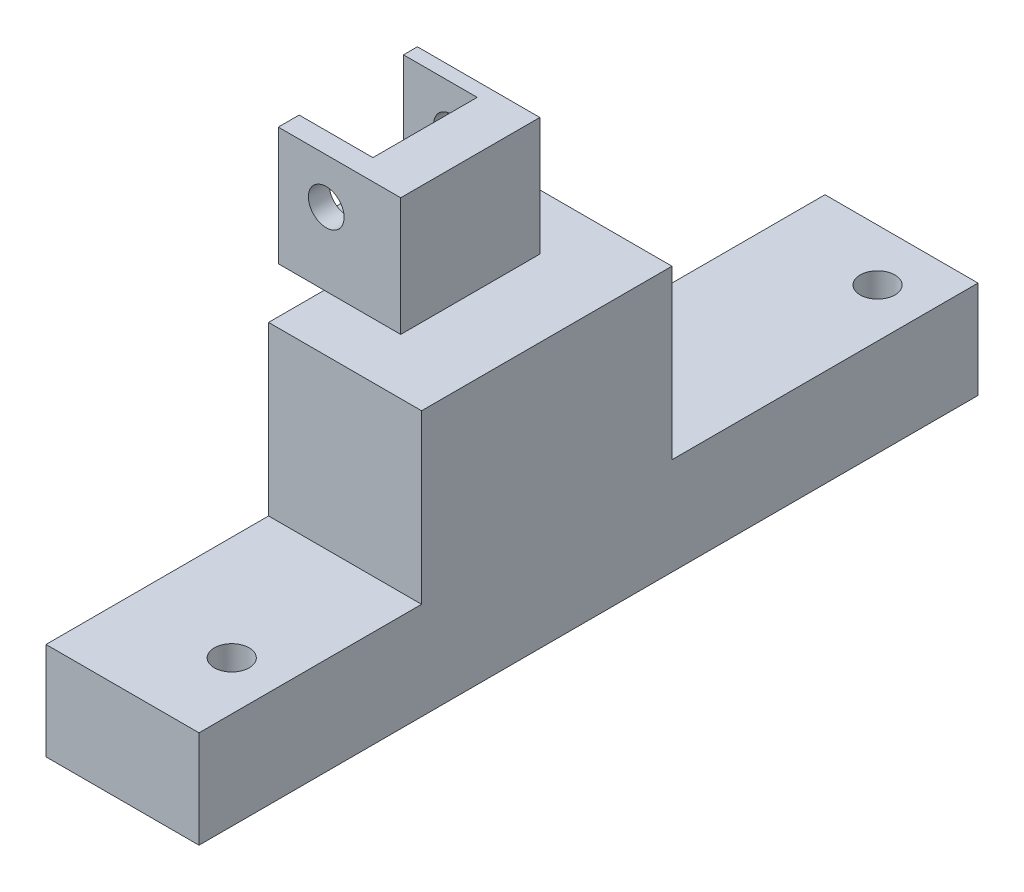
SolidWorks part; units mm, degrees
ref_plane "Front Plane" through (0, 0, 0) normal (0, 0, 1) x (1, 0, 0)
ref_plane "Top Plane" through (0, 0, 0) normal (0, 1, 0) x (1, 0, 0)
ref_plane "Right Plane" through (0, 0, 0) normal (1, 0, 0) x (0, 0, -1)
sketch "Sketch1" plane through (0, 0, 0) normal (0, 0, 1) x (1, 0, 0)
  line L0 (792.5838, 374.5748) -> (792.5838, 352.9594)
  line L1 (806.0458, 374.5748) -> (775.9383, 374.5748) construction
  line L2 (792.5838, 352.9594) -> (814.9358, 352.9594)
  line L3 (814.9358, 352.9594) -> (814.9358, 374.5748)
  line L4 (814.9358, 374.5748) -> (792.5838, 374.5748)
  line L5 (792.5838, 356.7694) -> (801.3383, 356.7694)
  line L6 (801.3383, 356.7694) -> (791.1783, 356.7694) construction
  circle A1 centre (801.3383, 366.2944) radius 3.2639
  arc A2 (801.3383, 356.7694) -> (806.0458, 358.014) centre (801.3383, 366.2944) ccw
  arc A3 (806.0458, 358.014) -> (806.0458, 374.5748) centre (801.3383, 366.2944) ccw
  dimension "D4" = 6.5278
  dimension "D1" = 3.81
  dimension "D2" = 22.352
  dimension "D3" = 8.89
extrude "Boss-Extrude1" add sketch "Sketch1" against normal blind 21.59 contours A3 A2 L5 L0 L2 L3 L4
sketch "Sketch2" plane through (0, 0, 0) normal (0, 0, 1) x (1, 0, 0)
  line L0 (792.5838, 352.9594) -> (792.5838, 374.5748)
  line L1 (806.0458, 374.5748) -> (775.9383, 374.5748) construction
  line L2 (792.5838, 374.5748) -> (814.9358, 374.5748)
  line L3 (814.9358, 374.5748) -> (814.9358, 352.9594)
  line L4 (814.9358, 352.9594) -> (792.5838, 352.9594)
  circle A0 centre (801.3383, 366.2944) radius 3.2639
  dimension "D1" = 6.5278
extrude "Boss-Extrude2" add sketch "Sketch2" along normal blind 3.81
sketch "Sketch3" plane through (0, 0, -21.59) normal (0, 0, -1) x (-1, 0, 0)
  line L0 (-792.5838, 356.7694) -> (-792.5838, 374.5748)
  line L1 (-792.5838, 374.5748) -> (-806.0458, 374.5748)
  line L2 (-792.5838, 356.7694) -> (-801.3383, 356.7694) construction
  line L3 (-801.3383, 356.7694) -> (-792.5838, 356.7694)
  arc A0 (-806.0458, 374.5748) -> (-801.3383, 356.7694) centre (-801.3383, 366.2944) ccw
  arc A1 (-806.0458, 358.014) -> (-801.3383, 356.7694) centre (-801.3383, 366.2944) ccw construction
  circle A2 centre (-801.3383, 366.2944) radius 3.2639
  dimension "D1" = 6.5278
extrude "Boss-Extrude3" add sketch "Sketch3" against normal up to surface (2.54 mm away)
sketch "Sketch6" plane through (0, 352.9594, 0) normal (0, -1, 0) x (1, 0, 0)
  line L0 (800.9658, 54.61) -> (800.9658, -87.63)
  line L1 (800.9658, -87.63) -> (828.9058, -87.63)
  line L2 (828.9058, -87.63) -> (828.9058, 54.61)
  line L3 (828.9058, 54.61) -> (800.9658, 54.61)
  circle A0 centre (820.039, 39.7686) radius 3.175
  circle A1 centre (820.039, 39.7686) radius 3.175 construction
  circle A2 centre (820.039, -78.16) radius 3.175
  circle A3 centre (820.039, -78.16) radius 3.175 construction
  dimension "D2" = 6.35
  dimension "D3" = 6.35
  dimension "D1" = 27.94
  dimension "D4" = 66.04
  dimension "D5" = 50.8
  dimension "D6" = 13.97
extrude "Boss-Extrude4" add sketch "Sketch6" along normal up to surface (48.388 mm away)
sketch "Sketch7" plane through (828.9058, 0, 0) normal (1, 0, 0) x (0, 0, -1)
  line L0 (-54.61, 322.3514) -> (-13.97, 322.3514)
  line L1 (-54.61, 304.5714) -> (-54.61, 352.9594) construction
  line L2 (-13.97, 322.3514) -> (-13.97, 352.9594)
  line L3 (87.63, 352.9594) -> (-54.61, 352.9594) construction
  line L4 (-13.97, 352.9594) -> (-54.61, 352.9594)
  line L5 (-54.61, 352.9594) -> (-54.61, 322.3514)
  line L6 (31.75, 352.9594) -> (31.75, 322.3514)
  line L7 (31.75, 322.3514) -> (87.63, 322.3514)
  line L8 (87.63, 304.5714) -> (87.63, 352.9594) construction
  line L9 (87.63, 322.3514) -> (87.63, 352.9594)
  line L10 (87.63, 352.9594) -> (31.75, 352.9594)
  line L11 (-54.61, 304.5714) -> (87.63, 304.5714) construction
  dimension "D1" = 17.78
  dimension "D2" = 40.64
  dimension "D3" = 55.88
  dimension "D4" = 17.78
extrude "Cut-Extrude1" cut sketch "Sketch7" against normal blind 30.226
